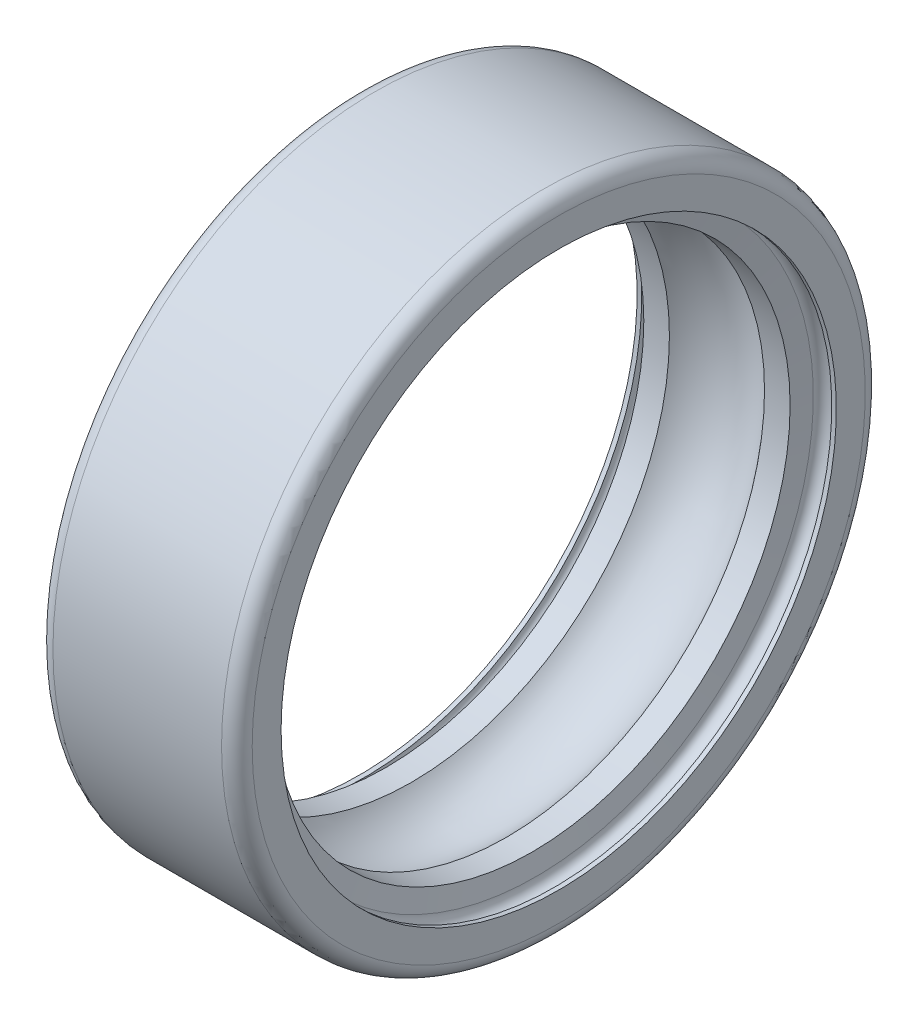
SolidWorks part; units mm, degrees
ref_plane "Front Plane" through (0, 0, 0) normal (0, 0, 1) x (1, 0, 0)
ref_plane "Top Plane" through (0, 0, 0) normal (0, 1, 0) x (1, 0, 0)
ref_plane "Right Plane" through (0, 0, 0) normal (1, 0, 0) x (0, 0, -1)
ref_plane "Plane1"
sketch "Sketch1" plane through (0, 0, 0) normal (0, 0, 1) x (1, 0, 0)
  line L0 (0, 18.115) -> (0.3, 18.115)
  line L1 (1.5, 18.115) -> (1.7275, 16.825)
  line L2 (1.7275, 16.825) -> (3.3972, 16.825)
  line L3 (9.6028, 16.825) -> (11.2725, 16.825)
  line L4 (11.2725, 16.825) -> (11.5, 18.115)
  line L5 (12.7, 18.115) -> (13, 18.115)
  line L6 (13, 18.115) -> (13, 20)
  line L7 (12, 21) -> (1, 21)
  line L8 (0, 20) -> (0, 18.115)
  line L9 (50, 0) -> (-50, 0) construction
  arc A0 (1.5, 18.115) -> (0.3, 18.115) centre (0.9, 18.115) ccw
  arc A1 (9.6028, 16.825) -> (3.3972, 16.825) centre (6.5, 14.35) ccw
  arc A2 (12.7, 18.115) -> (11.5, 18.115) centre (12.1, 18.115) ccw
  arc A3 (13, 20) -> (12, 21) centre (12, 20) ccw
  arc A4 (1, 21) -> (0, 20) centre (1, 20) ccw
revolve "Revolução1" add sketch "Sketch1" angle 360 about L9
